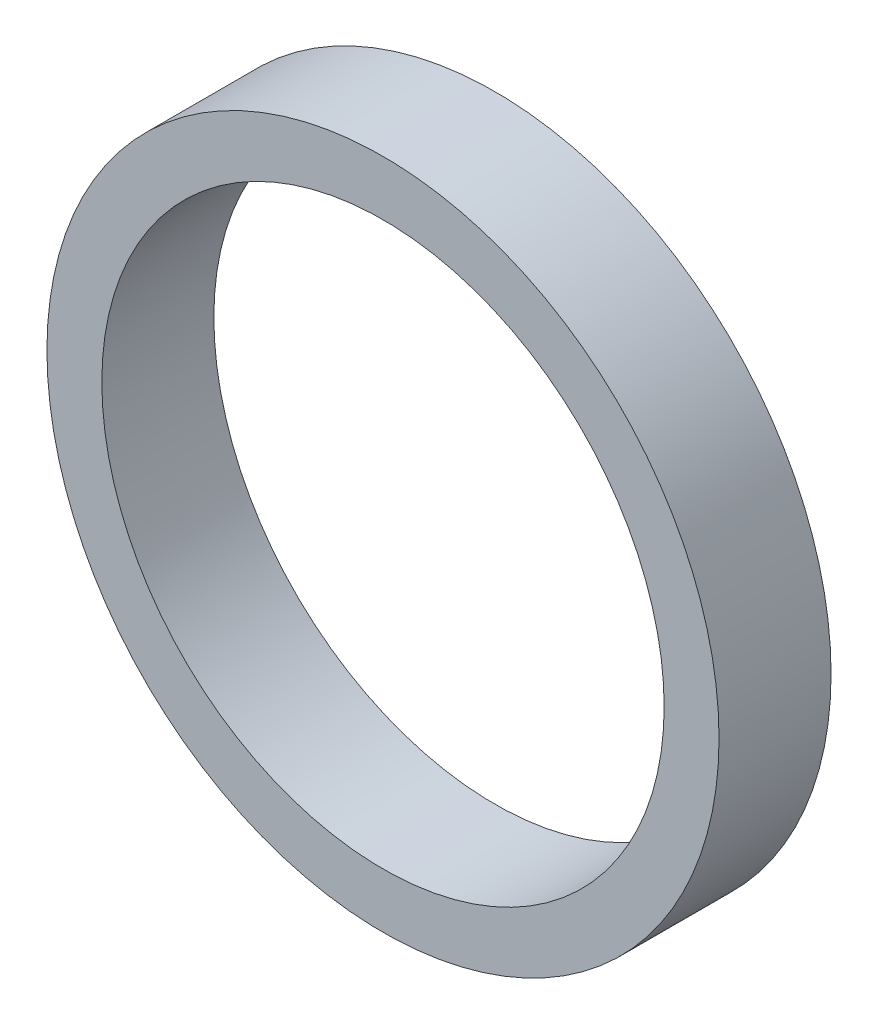
SolidWorks part; units mm, degrees
ref_plane "Front Plane" through (0, 0, 0) normal (0, 0, 1) x (1, 0, 0)
ref_plane "Top Plane" through (0, 0, 0) normal (0, 1, 0) x (1, 0, 0)
ref_plane "Right Plane" through (0, 0, 0) normal (1, 0, 0) x (0, 0, -1)
sketch "Sketch1" plane through (0, 0, 0) normal (0, 0, 1) x (1, 0, 0)
  circle A0 centre (0, 0) radius 19.05
  circle A1 centre (0, 0) radius 15.9385
  dimension "D1" = 38.1
  dimension "ID" = 31.877
extrude "Extrude1" add sketch "Sketch1" along normal mid plane 6.35
sketch "Sketch2" plane through (0, 0, 0) normal (1, 0, 0) x (0, 0, -1)
  line L0 (-3.175, -15.9385) -> (3.175, -15.9385) construction
  line L3 (3.175, 15.9385) -> (-3.175, 15.9385) construction
  line L5 (-3.175, -15.9385) -> (3.175, -15.9385)
  line L6 (3.175, 15.9385) -> (-3.175, 15.9385)
sketch "Sketch4" plane through (0, 0, 3.175) normal (0, 0, 1) x (1, 0, 0)
  line L0 (0, 0) -> (-11.2702, 11.2702)
  line L1 (0, -55) -> (0, 55) construction
  circle A0 centre (0, 0) radius 15.9385 construction
  dimension "D1" = 45
